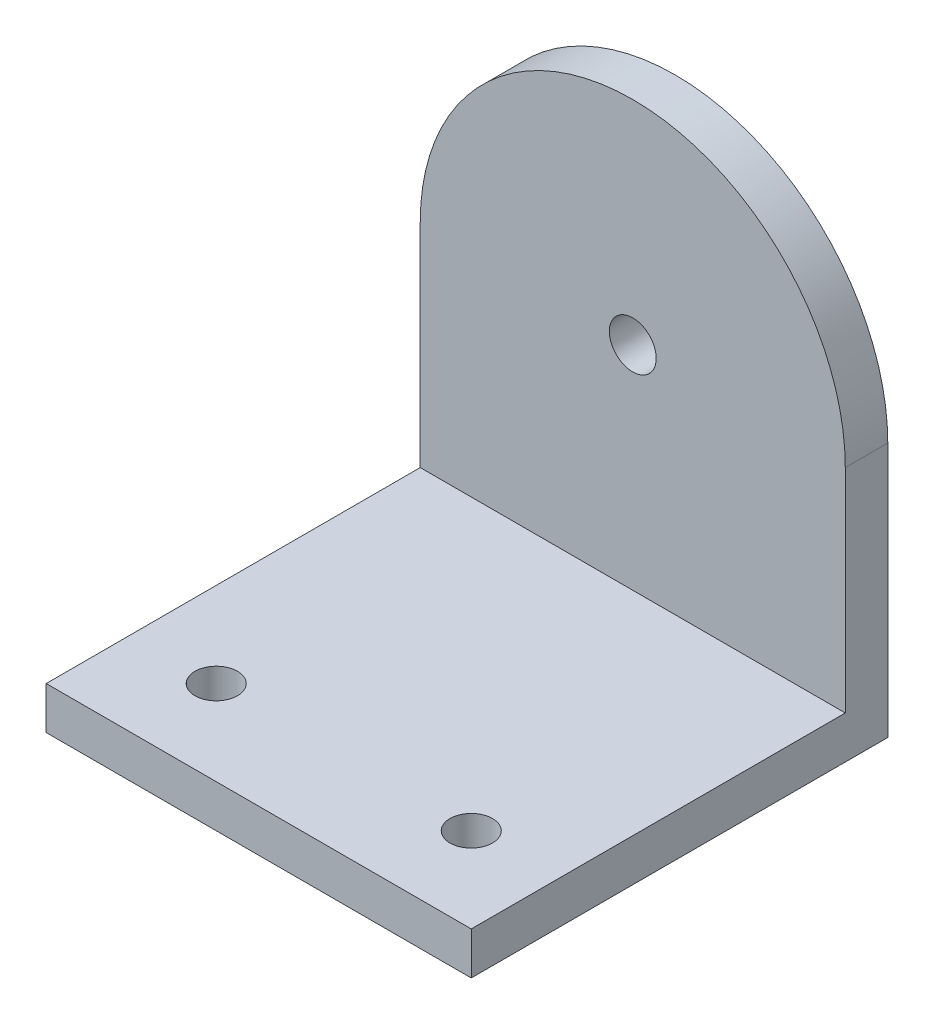
SolidWorks part; units mm, degrees
ref_plane "Front Plane" through (0, 0, 0) normal (0, 0, 1) x (1, 0, 0)
ref_plane "Top Plane" through (0, 0, 0) normal (0, 1, 0) x (1, 0, 0)
ref_plane "Right Plane" through (0, 0, 0) normal (1, 0, 0) x (0, 0, -1)
sketch "Sketch1" plane through (0, 0, 0) normal (0, 0, 1) x (1, 0, 0)
  line L1 (-15.875, 0) -> (15.875, 0)
  line L2 (-15.875, 0) -> (-15.875, -19.05)
  line L3 (-15.875, -19.05) -> (15.875, -19.05)
  line L4 (15.875, 0) -> (15.875, -19.05)
  circle A0 centre (0, 0) radius 15.875
  arc A2 (-15.875, 0) -> (15.875, 0) centre (0, 0) ccw
  dimension "D1" = 31.75
  dimension "D2" = 19.05
extrude "Boss-Extrude1" add sketch "Sketch1" along normal blind 3.175
sketch "Sketch4" plane through (0, 0, 3.175) normal (0, 0, 1) x (1, 0, 0)
  line L0 (15.875, 0) -> (15.875, -19.05) construction
  line L1 (-15.875, -19.05) -> (15.875, -19.05)
  line L2 (-15.875, -19.05) -> (-15.875, -15.875)
  line L3 (-15.875, -15.875) -> (15.875, -15.875)
  line L4 (15.875, -19.05) -> (15.875, -15.875)
  dimension "D1" = 3.175
extrude "Boss-Extrude2" add sketch "Sketch4" along normal blind 27.94
sketch "Sketch5" plane through (0, -15.875, 0) normal (0, 1, 0) x (1, 0, 0)
  line L0 (-15.875, -24.765) -> (15.875, -24.765) construction
  line L2 (-15.875, -31.115) -> (-15.875, -3.175) construction
  line L3 (0, -3.175) -> (0, -31.115) construction
  line L4 (15.875, -3.175) -> (-15.875, -3.175) construction
  line L5 (15.875, -31.115) -> (-15.875, -31.115) construction
  line L6 (15.875, -31.115) -> (15.875, -3.175) construction
  circle A0 centre (-9.525, -24.765) radius 1.5875
  circle A1 centre (9.525, -24.765) radius 1.5875
  dimension "D1" = 3.175
  dimension "D2" = 9.525
  dimension "D3" = 6.35
extrude "Cut-Extrude2" cut sketch "Sketch5" against normal through all
sketch "Sketch6" plane through (0, 0, 3.175) normal (0, 0, 1) x (1, 0, 0)
  circle A0 centre (0, 0) radius 1.75
  dimension "D1" = 3.5
extrude "Cut-Extrude3" cut sketch "Sketch6" against normal through all
